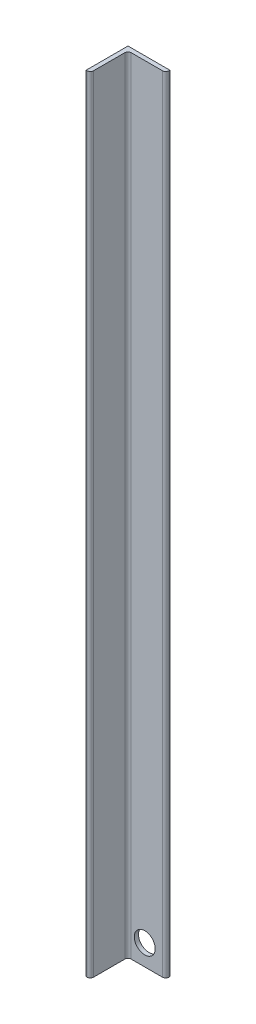
SolidWorks part; units mm, degrees
material "ASTM A36 Steel"
ref_plane "Front Plane" through (0, 0, 0) normal (0, 0, 1) x (1, 0, 0)
ref_plane "Top Plane" through (0, 0, 0) normal (0, 1, 0) x (1, 0, 0)
ref_plane "Right Plane" through (0, 0, 0) normal (1, 0, 0) x (0, 0, -1)
sketch "Sketch1" plane through (0, 0, 0) normal (0, 1, 0) x (1, 0, 0)
  line L0 (-27.4999, 29.2132) -> (-67.4999, 29.2132)
  line L1 (-67.4999, 29.2132) -> (-67.4999, -10.7868)
  line L2 (-67.4999, -10.7868) -> (-66.4999, -10.7868)
  line L3 (-63.4999, -7.7868) -> (-63.4999, 22.2132)
  line L4 (-60.4999, 25.2132) -> (-30.4999, 25.2132)
  line L5 (-27.4999, 28.2132) -> (-27.4999, 29.2132)
  arc A0 (-66.4999, -10.7868) -> (-63.4999, -7.7868) centre (-66.4999, -7.7868) ccw
  arc A1 (-63.4999, 22.2132) -> (-60.4999, 25.2132) centre (-60.4999, 22.2132) cw
  arc A2 (-30.4999, 25.2132) -> (-27.4999, 28.2132) centre (-30.4999, 28.2132) ccw
  point P8 (-63.4999, -10.7868)
  point P13 (-27.4999, 25.2132)
  dimension "D5" = 3
  dimension "D1" = 40
  dimension "D2" = 40
  dimension "D3" = 4
  dimension "D4" = 4
extrude "Boss-Extrude1" add sketch "Sketch1" along normal blind 750
sketch "Sketch2" plane through (0, 0, -25.2132) normal (0, 0, 1) x (1, 0, 0)
  line L0 (-27.4999, 750) -> (-27.4999, 0) construction
  line L2 (-27.4999, 0) -> (-67.4999, 0) construction
  circle A0 centre (-47.4999, 20) radius 10
  dimension "D1" = 20
  dimension "D2" = 20
  dimension "D3" = 20
extrude "Cut-Extrude1" cut sketch "Sketch2" against normal through all
